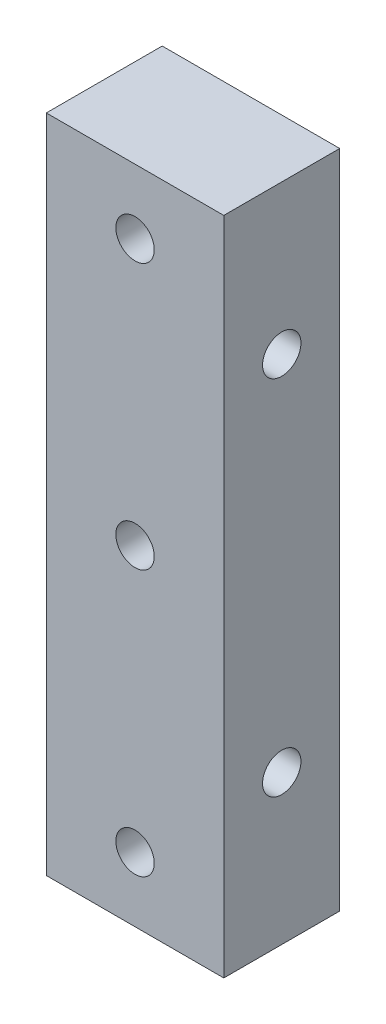
SolidWorks part; units mm, degrees
ref_plane "Front Plane" through (0, 0, 0) normal (0, 0, 1) x (1, 0, 0)
ref_plane "Top Plane" through (0, 0, 0) normal (0, 1, 0) x (1, 0, 0)
ref_plane "Right Plane" through (0, 0, 0) normal (1, 0, 0) x (0, 0, -1)
sketch "Sketch1" plane through (0, 0, 0) normal (0, 0, 1) x (1, 0, 0)
  line L1 (-9.3345, 34.7345) -> (9.3345, 34.7345)
  line L2 (-9.3345, 34.7345) -> (-9.3345, -34.7345)
  line L3 (-9.3345, -34.7345) -> (9.3345, -34.7345)
  line L4 (9.3345, 34.7345) -> (9.3345, -34.7345)
  line L5 (-9.3345, 34.7345) -> (9.3345, -34.7345) construction
  line L6 (-9.3345, -34.7345) -> (9.3345, 34.7345) construction
  point P0 (0, 0)
  dimension "D1" = 18.669
  dimension "D2" = 69.469
extrude "Boss-Extrude1" add sketch "Sketch1" along normal blind 12.192
sketch "Sketch2" plane through (9.3345, 0, 0) normal (1, 0, 0) x (0, 0, -1)
  line L0 (-6.096, 19.05) -> (-6.096, -19.05) construction
  line L2 (0, -34.7345) -> (0, 34.7345) construction
  line L3 (-12.192, 34.7345) -> (0, 34.7345) construction
  point P2 (-6.096, 0)
  point P3 (-6.096, 34.7345)
  point P7 (0, 0)
  dimension "D2" = 38.1
hole_wizard "Tap Drill for #10-32 Tap1" positions "Sketch3" profile "Sketch4" hole size "#10-32" standard "ANSI Inch" end condition through all
sketch "Sketch3" plane through (9.3345, 0, 0) normal (1, 0, 0) x (0, 0, -1)
  point P0 (-6.096, 19.05)
  point P3 (-6.096, -19.05)
sketch "Sketch4" plane through (9.3345, 19.05, 6.096) normal (0, 1, 0) x (0, 0, -1)
  line L0 (0, 0) -> (0, 18.669)
  line L1 (0, 18.669) -> (2.0193, 18.669)
  line L2 (2.0193, 18.669) -> (2.0193, 0)
  line L5 (2.0193, 0) -> (0, 0)
  line L11 (0, -6.35) -> (0, 107.95) construction
  dimension "Thru Hole Dia." = 4.0386
  dimension "Thru Hole Depth" = 18.669
sketch "Sketch5" plane through (0, 0, 12.192) normal (0, 0, 1) x (1, 0, 0)
  line L0 (0, 27.94) -> (0, -27.94) construction
  point P3 (0, 0)
  dimension "D1" = 55.88
hole_wizard "Tap Drill for #10-32 Tap2" positions "Sketch6" profile "Sketch8" hole size "#10-32" standard "ANSI Inch" end condition through all
sketch "Sketch6" plane through (0, 0, 12.192) normal (0, 0, 1) x (1, 0, 0)
  point P0 (0, 27.94)
  point P3 (0, -27.94)
  point P7 (0, 0)
sketch "Sketch8" plane through (0, 27.94, 12.192) normal (1, 0, 0) x (0, -1, 0)
  line L0 (0, 0) -> (0, 12.192)
  line L1 (0, 12.192) -> (2.0193, 12.192)
  line L2 (2.0193, 12.192) -> (2.0193, 0)
  line L5 (2.0193, 0) -> (0, 0)
  line L11 (0, -6.35) -> (0, 107.95) construction
  dimension "Thru Hole Dia." = 4.0386
  dimension "Thru Hole Depth" = 12.192
sketch "Sketch9" plane through (0, -34.7345, 0) normal (0, -1, 0) x (1, 0, 0)
  line L0 (-9.3345, 12.192) -> (9.3345, 12.192) construction
  line L1 (-9.3345, 0) -> (9.3345, 0) construction
  point P0 (0, -6.858)
  point P4 (0, 0)
  dimension "D1" = 19.05
